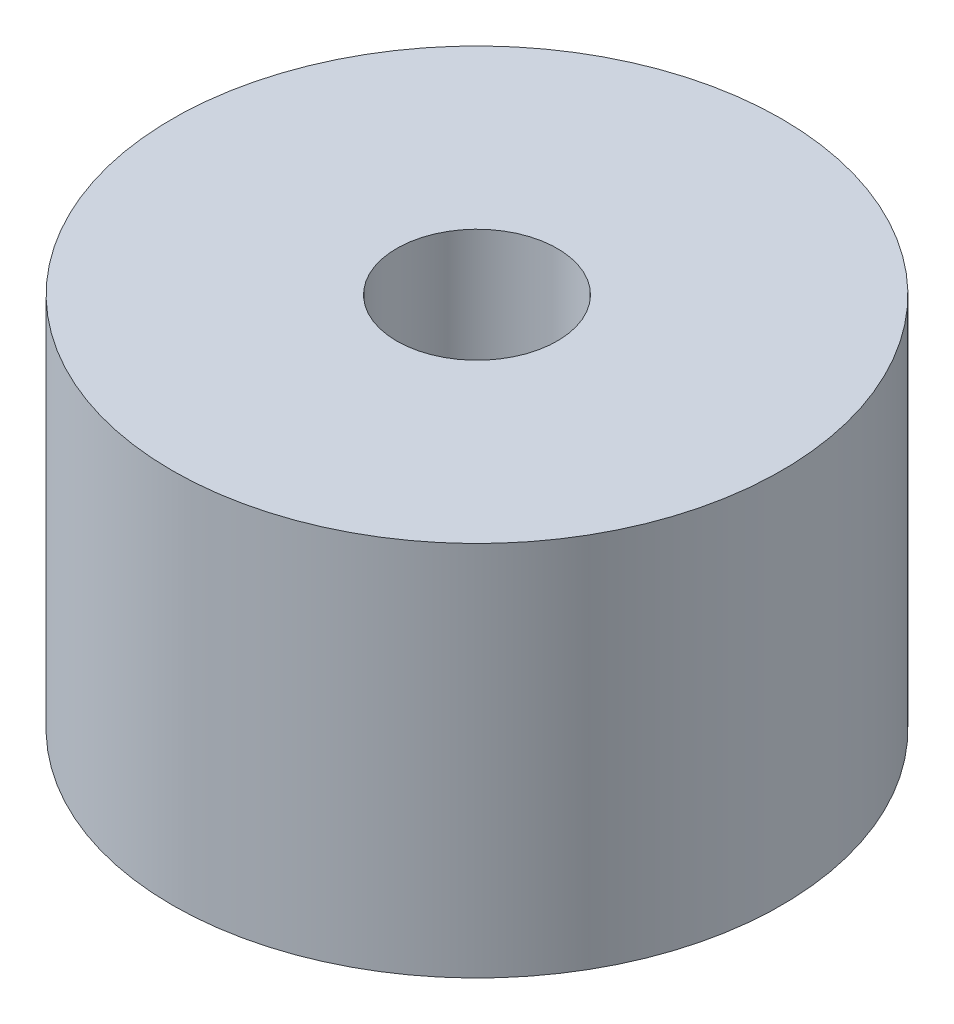
SolidWorks part; units mm, degrees
ref_plane "Front Plane" through (0, 0, 0) normal (0, 0, 1) x (1, 0, 0)
ref_plane "Top Plane" through (0, 0, 0) normal (0, 1, 0) x (1, 0, 0)
ref_plane "Right Plane" through (0, 0, 0) normal (1, 0, 0) x (0, 0, -1)
sketch "Sketch1" plane through (0, 0, 0) normal (0, 1, 0) x (1, 0, 0)
  circle A0 centre (0, 0) radius 8.825
  circle A1 centre (0, 0) radius 2.325
  dimension "D1" = 17.65
  dimension "D2" = 4.65
extrude "Boss-Extrude1" add sketch "Sketch1" along normal blind 10.9
